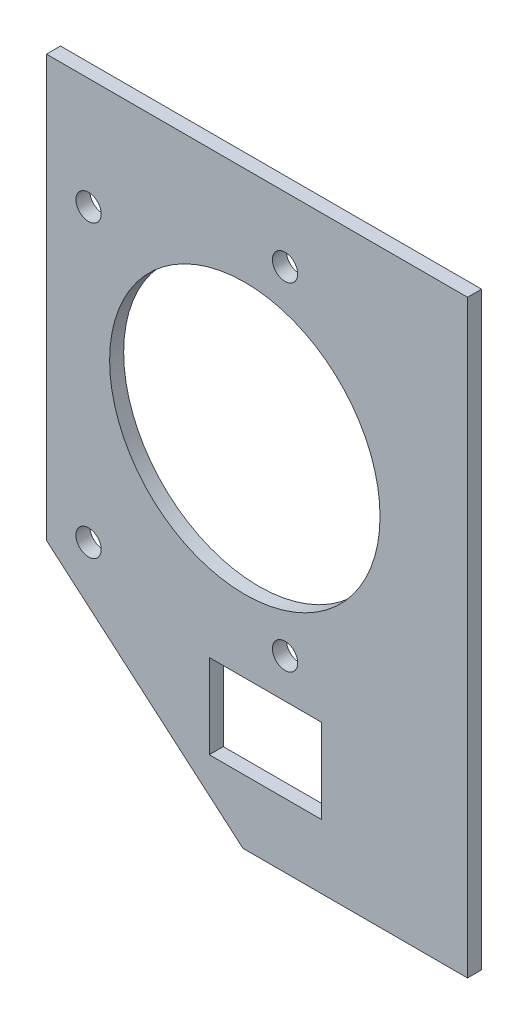
SolidWorks part; units mm, degrees
ref_plane "Plan de face" through (0, 0, 0) normal (0, 0, 1) x (1, 0, 0)
ref_plane "Plan de dessus" through (0, 0, 0) normal (0, 1, 0) x (1, 0, 0)
ref_plane "Plan de droite" through (0, 0, 0) normal (1, 0, 0) x (0, 0, -1)
sketch "Esquisse1" plane through (0, 0, 0) normal (0, 0, 1) x (1, 0, 0)
  line L1 (0, 0) -> (150, 0)
  line L2 (0, 0) -> (0, -210)
  line L3 (0, -210) -> (150, -210)
  line L4 (150, 0) -> (150, -210)
  dimension "D1" = 150
  dimension "D2" = 210
extrude "Boss.-Extru.1" add sketch "Esquisse1" along normal blind 5
hole_wizard "Dégagement M81" positions "Esquisse4" profile "Esquisse3" hole size "M8" standard "ISO" end condition through all
sketch "Esquisse4" plane through (0, 0, 5) normal (0, 0, 1) x (1, 0, 0)
  line L0 (150, -210) -> (150, 0) construction
  point P0 (85, -23.1209)
  point P9 (85, -143.1209)
  point P19 (15, -143.1209)
  point P27 (15, -39.6209)
  dimension "D1" = 65
  dimension "D2" = 65
  dimension "D3" = 120
  dimension "D4" = 70
  dimension "D5" = 120
  dimension "D6" = 103.5
sketch "Esquisse3" plane through (85, -23.1209, 5) normal (1, 0, 0) x (0, -1, 0)
  line L0 (0, 0) -> (0, 5)
  line L1 (0, 5) -> (4.5, 5)
  line L2 (4.5, 5) -> (4.5, 0)
  line L5 (4.5, 0) -> (0, 0)
  line L11 (0, -6.35) -> (0, 107.95) construction
  dimension "Diamètre du perçage jusqu'au prochain" = 9
  dimension "Profondeur du perçage jusqu'au prochain" = 5
sketch "Esquisse5" plane through (0, 0, 5) normal (0, 0, 1) x (1, 0, 0)
  line L1 (98, -157.1209) -> (58, -157.1209)
  line L2 (98, -157.1209) -> (98, -187.1209)
  line L3 (98, -187.1209) -> (58, -187.1209)
  line L4 (58, -157.1209) -> (58, -187.1209)
  circle A0 centre (85, -143.1209) radius 4.5 construction
  dimension "D1" = 40
  dimension "D2" = 13
  dimension "D3" = 30
  dimension "D4" = 14
extrude "Enlèv. mat.-Extru.1" cut sketch "Esquisse5" against normal blind 5
sketch "Esquisse6" plane through (0, 0, 5) normal (0, 0, 1) x (1, 0, 0)
  line L0 (0, -210) -> (0, -150)
  line L1 (0, 0) -> (0, -210) construction
  line L2 (0, -150) -> (70, -210)
  line L3 (0, -210) -> (150, -210) construction
  line L4 (70, -210) -> (0, -210)
  dimension "D1" = 60
  dimension "D2" = 70
extrude "Enlèv. mat.-Extru.2" cut sketch "Esquisse6" against normal blind 5 contours L2 L4 L0
sketch "Esquisse7" plane through (0, 0, 5) normal (0, 0, 1) x (1, 0, 0)
  circle A0 centre (70.6678, -83.1945) radius 48.1568
  point P2 (60.5592, -82.6168)
  point P3 (0, 0)
  point P4 (70.6678, -83.1945)
extrude "Enlèv. mat.-Extru.3" cut sketch "Esquisse7" against normal blind 5 contours A0
